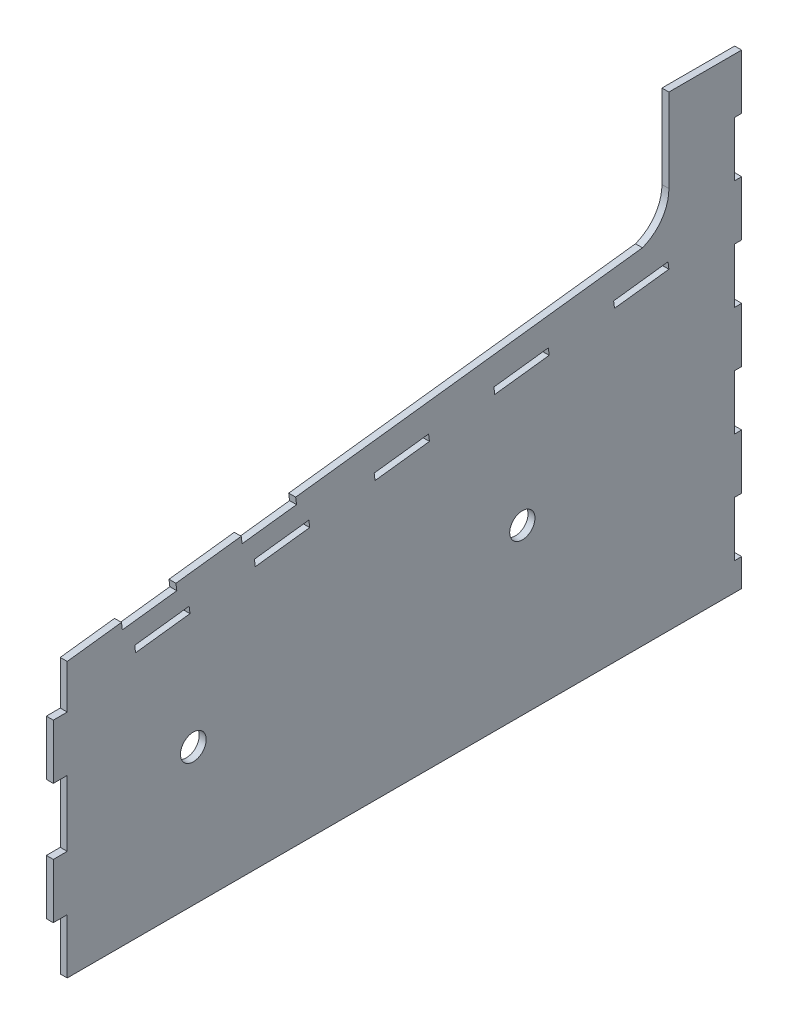
SolidWorks part; units mm, degrees
material "Beech"
ref_plane "Front Plane" through (0, 0, 0) normal (0, 0, 1) x (1, 0, 0)
ref_plane "Top Plane" through (0, 0, 0) normal (0, 1, 0) x (1, 0, 0)
ref_plane "Right Plane" through (0, 0, 0) normal (1, 0, 0) x (0, 0, -1)
sketch "Sketch1" plane through (0, 0, 0) normal (1, 0, 0) x (0, 0, -1)
  line L1 (0, 0) -> (615, 0)
  line L2 (0, 0) -> (0, 50)
  line L7 (615, 425.32) -> (548.65, 425.32)
  line L8 (548.65, 349.09) -> (548.65, 425.32)
  line L9 (0, 250) -> (615, 250) construction
  line L10 (524.53, 314.4042) -> (615, 325.5125) construction
  line L11 (-12.7, 160) -> (-12.7, 210)
  line L12 (0, 50) -> (-12.7, 50)
  line L14 (0, 100) -> (-12.7, 100)
  line L15 (-12.7, 50) -> (-12.7, 100)
  line L16 (0, 160) -> (-12.7, 160)
  line L18 (0, 210) -> (-12.7, 210)
  line L19 (0, 210) -> (0, 250)
  line L21 (0, 100) -> (0, 160)
  line L33 (0, 250) -> (524.53, 314.4042) construction
  line L34 (0, 250) -> (524.53, 314.4042)
  line L52 (615, 425.32) -> (615, 0)
  arc A0 (524.53, 314.4042) -> (548.65, 349.09) centre (511.65, 349.09) ccw
  dimension "D4" = 37
  dimension "D1" = 615
  dimension "D2" = 250
  dimension "D3" = 66.35
  dimension "D5" = 7
  dimension "D6" = 175.32
  dimension "D7" = 76.23
  dimension "D8" = 12.7
  dimension "D9" = 50
  dimension "D10" = 50
  dimension "D11" = 2
  dimension "D12" = 40
extrude "Boss-Extrude1" add sketch "Sketch1" along normal blind 6.35
sketch "Sketch2" plane through (6.35, 0, 0) normal (1, 0, 0) x (0, 0, -1)
  line L0 (514.5695, 313.1812) -> (615, 324.7758) construction
  line L2 (208.3168, 275.5781) -> (158.6895, 269.4846)
  line L3 (0, 224.4093) -> (615, 299.9218) construction
  line L4 (0, 50) -> (0, 0) construction
  line L5 (61.5379, 231.9651) -> (62.3117, 225.6625)
  line L6 (62.3117, 225.6625) -> (111.939, 231.7559)
  line L7 (111.939, 231.7559) -> (111.1652, 238.0586)
  line L8 (111.1652, 238.0586) -> (61.5379, 231.9651)
  line L9 (220.3452, 251.4642) -> (170.7179, 245.3708)
  line L10 (170.7179, 245.3708) -> (171.4918, 239.0681)
  line L11 (171.4918, 239.0681) -> (221.1191, 245.1616)
  line L12 (221.1191, 245.1616) -> (220.3452, 251.4642)
  line L13 (329.5253, 264.8699) -> (279.898, 258.7764)
  line L14 (279.898, 258.7764) -> (280.6719, 252.4737)
  line L15 (280.6719, 252.4737) -> (330.2992, 258.5672)
  line L16 (330.2992, 258.5672) -> (329.5253, 264.8699)
  line L17 (438.7054, 278.2755) -> (389.0781, 272.182)
  line L18 (389.0781, 272.182) -> (389.852, 265.8794)
  line L19 (389.852, 265.8794) -> (439.4793, 271.9728)
  line L20 (439.4793, 271.9728) -> (438.7054, 278.2755)
  line L21 (547.8855, 291.6811) -> (498.2582, 285.5877)
  line L22 (498.2582, 285.5877) -> (499.032, 279.285)
  line L23 (499.032, 279.285) -> (548.6593, 285.3785)
  line L24 (548.6593, 285.3785) -> (547.8855, 291.6811)
  line L25 (158.6895, 269.4846) -> (159.4634, 263.182)
  line L26 (524.53, 314.4042) -> (0, 250) construction
  line L27 (0, 224.4093) -> (-3.0955, 249.6199) construction
  line L28 (-3.0955, 249.6199) -> (0, 250) construction
  line L29 (49.5095, 256.079) -> (50.2833, 249.7763)
  line L30 (50.2833, 249.7763) -> (99.9106, 255.8698)
  line L31 (99.9106, 255.8698) -> (99.1368, 262.1725)
  line L32 (99.1368, 262.1725) -> (49.5095, 256.079)
  line L33 (159.4634, 263.182) -> (209.0907, 269.2754)
  line L34 (209.0907, 269.2754) -> (208.3168, 275.5781)
  line L35 (0, 0) -> (615, 0) construction
  line L37 (0, 160) -> (0, 100) construction
  line L38 (615, 0) -> (615, 425.32) construction
  line L39 (615, 425.32) -> (548.65, 425.32) construction
  line L40 (615, 375.32) -> (608.65, 375.32)
  line L41 (615, 375.32) -> (615, 325.32)
  line L42 (615, 325.32) -> (608.65, 325.32)
  line L43 (608.65, 375.32) -> (608.65, 325.32)
  line L56 (615, 275.32) -> (615, 225.32)
  line L57 (615, 275.32) -> (608.65, 275.32)
  line L58 (608.65, 275.32) -> (608.65, 225.32)
  line L59 (615, 225.32) -> (608.65, 225.32)
  line L60 (615, 175.32) -> (615, 125.32)
  line L61 (615, 175.32) -> (608.65, 175.32)
  line L62 (608.65, 175.32) -> (608.65, 125.32)
  line L63 (615, 125.32) -> (608.65, 125.32)
  line L64 (615, 75.32) -> (615, 25.32)
  line L65 (615, 75.32) -> (608.65, 75.32)
  line L66 (608.65, 75.32) -> (608.65, 25.32)
  line L67 (615, 25.32) -> (608.65, 25.32)
  circle A0 centre (415, 150) radius 11.5
  circle A1 centre (115, 125) radius 11.735
  dimension "D12" = 23
  dimension "D13" = 23.47
  dimension "D1" = 25.4
  dimension "D2" = 50
  dimension "D3" = 6.35
  dimension "D4" = 62
  dimension "D5" = 90
  dimension "D6" = 6.35
  dimension "D7" = 53
  dimension "D8" = 50
  dimension "D10" = 150
  dimension "D11" = 200
  dimension "D14" = 115
  dimension "D15" = 125
  dimension "D16" = 6.35
  dimension "D17" = 50
  dimension "D18" = 50
  dimension "D9" = 2
extrude "Cut-Extrude1" cut sketch "Sketch2" against normal blind 6.35
